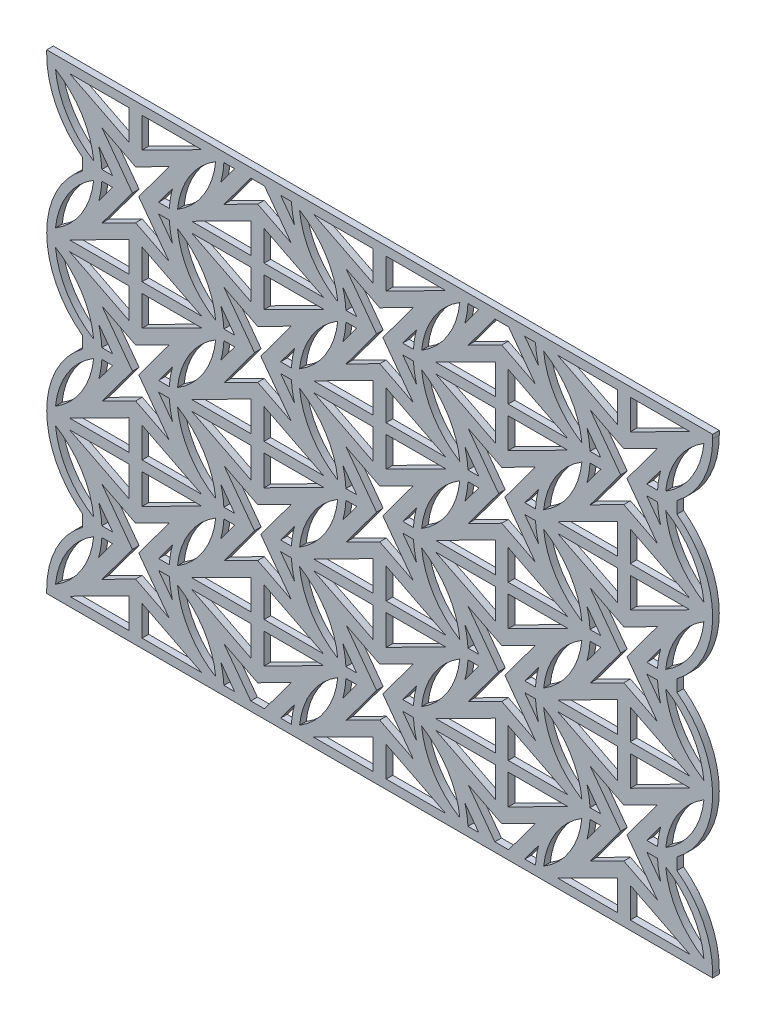
SolidWorks part; units mm, degrees
ref_plane "Front Plane" through (0, 0, 0) normal (0, 0, 1) x (1, 0, 0)
ref_plane "Top Plane" through (0, 0, 0) normal (0, 1, 0) x (1, 0, 0)
ref_plane "Right Plane" through (0, 0, 0) normal (1, 0, 0) x (0, 0, -1)
sketch "Sketch1" plane through (0, 0, 0) normal (0, 0, 1) x (1, 0, 0)
  line L1 (2.9839, -0.0761) -> (4.9328, -0.0761)
  line L3 (-17.2822, 14.8186) -> (-17.2822, 15.535) construction
  line L6 (14.9178, 15.535) -> (14.9178, 14.8186) construction
  line L8 (-5.3484, -0.0761) -> (-7.2973, -0.0761)
  line L9 (-17.2822, -13.1337) -> (-17.2822, -13.8502)
  line L10 (-5.3484, 1.761) -> (-7.8631, 5.1578)
  line L11 (-17.2822, -13.8502) -> (14.9178, -13.8502)
  line L13 (-10.8207, 1.9225) -> (-10.8207, -0.2376)
  line L16 (-17.2822, 14.8186) -> (14.9178, 14.8186) construction
  line L17 (10.7818, 13.9) -> (-0.0088, 13.9)
  line L21 (2.9839, 1.761) -> (5.4987, 5.1578)
  line L23 (-2.3557, 8.4501) -> (-13.1463, 13.9)
  line L24 (2.9839, -0.0761) -> (5.4987, -3.473)
  line L25 (2.9839, 1.761) -> (4.9328, 1.761)
  line L27 (-5.3484, -0.0761) -> (-7.8631, -3.473)
  line L28 (-5.3484, 1.761) -> (-7.2973, 1.761)
  line L30 (-17.2822, 15.535) -> (14.9178, 15.535) construction
  line L31 (-2.3557, 13.9) -> (-13.1463, 13.9)
  line L33 (14.9178, -13.8502) -> (14.9178, -13.1337) construction
  line L34 (-17.2822, -13.1337) -> (14.9178, -13.1337) construction
  line L36 (8.4563, 1.9225) -> (8.4563, -0.2376) construction
  line L40 (-0.0088, 8.4501) -> (10.7818, 13.9)
  line L41 (-1.1822, -3.5434) -> (4.9079, -6.6193)
  line L42 (4.9079, -6.6193) -> (-0.6161, 0.8424)
  line L43 (4.9079, 8.3041) -> (-0.6161, 0.8424)
  line L44 (-1.1822, 5.2282) -> (4.9079, 8.3041)
  line L45 (-1.1822, 5.2282) -> (-7.2724, 8.3041)
  line L46 (-7.2724, 8.3041) -> (-1.7483, 0.8424)
  line L47 (-7.2724, -6.6193) -> (-1.7483, 0.8424)
  line L48 (-1.1822, -3.5434) -> (-7.2724, -6.6193)
  line L49 (-1.7483, 0.8424) -> (49998.2517, 0.8424) construction
  line L50 (-1.1822, -3.5434) -> (-1.1822, 49996.4566) construction
  line L51 (-2.3557, 13.9) -> (-2.3557, 8.4501)
  line L52 (-0.0088, 13.9) -> (-0.0088, 8.4501)
  line L53 (-0.0088, -12.2152) -> (-0.0088, -6.7652)
  line L54 (10.7818, -12.2152) -> (-0.0088, -12.2152)
  line L55 (-0.0088, -6.7652) -> (10.7818, -12.2152)
  line L56 (-2.3557, -12.2152) -> (-2.3557, -6.7652)
  line L57 (-2.3557, -12.2152) -> (-13.1463, -12.2152)
  line L58 (-2.3557, -6.7652) -> (-13.1463, -12.2152)
  line L59 (32.8893, 27.8762) -> (22.0987, 27.8762)
  line L60 (32.8893, 1.761) -> (22.0987, 1.761)
  line L61 (37.0252, 29.5111) -> (37.0252, 28.7947) construction
  line L62 (19.7518, 27.8762) -> (8.9612, 27.8762)
  line L63 (19.7518, 27.8762) -> (19.7518, 22.4262)
  line L64 (4.8252, 0.126) -> (37.0252, 0.126) construction
  line L65 (16.7591, 13.9) -> (14.2443, 10.5031)
  line L66 (16.7591, 15.7371) -> (14.8102, 15.7371)
  line L67 (19.7518, 1.761) -> (8.9612, 1.761)
  line L68 (4.8252, 0.8424) -> (37.0252, 0.8424) construction
  line L69 (20.9252, 19.2043) -> (27.0154, 22.2802)
  line L70 (4.8252, 28.7947) -> (4.8252, 29.5111) construction
  line L71 (20.9252, 10.4328) -> (27.0154, 7.3569)
  line L72 (22.0987, 27.8762) -> (22.0987, 22.4262)
  line L73 (14.8351, 22.2802) -> (20.3591, 14.8186)
  line L74 (19.7518, 22.4262) -> (8.9612, 27.8762)
  line L75 (20.9252, 10.4328) -> (14.8351, 7.3569)
  line L76 (30.5638, 15.8986) -> (30.5638, 13.7385) construction
  line L77 (25.0914, 15.7371) -> (27.0403, 15.7371)
  line L78 (4.8252, 0.8424) -> (4.8252, 0.126) construction
  line L79 (25.0914, 13.9) -> (27.6061, 10.5031)
  line L80 (22.0987, 1.761) -> (22.0987, 7.2109)
  line L81 (11.2867, 15.8986) -> (11.2867, 13.7385) construction
  line L82 (25.0914, 15.7371) -> (27.6061, 19.134)
  line L83 (19.7518, 1.761) -> (19.7518, 7.2109)
  line L84 (37.0252, 0.126) -> (37.0252, 0.8424) construction
  line L85 (16.7591, 13.9) -> (14.8102, 13.9)
  line L86 (16.7591, 15.7371) -> (14.2443, 19.134)
  line L87 (22.0987, 7.2109) -> (32.8893, 1.761)
  line L88 (25.0914, 13.9) -> (27.0403, 13.9)
  line L89 (27.0154, 7.3569) -> (21.4913, 14.8186)
  line L90 (20.9252, 19.2043) -> (14.8351, 22.2802)
  line L91 (19.7518, 7.2109) -> (8.9612, 1.761)
  line L92 (4.8252, 28.7947) -> (37.0252, 28.7947) construction
  line L93 (22.0987, 22.4262) -> (32.8893, 27.8762)
  line L94 (27.0154, 22.2802) -> (21.4913, 14.8186)
  line L95 (14.8351, 7.3569) -> (20.3591, 14.8186)
  line L96 (4.8252, 29.5111) -> (37.0252, 29.5111) construction
  line L97 (54.9967, 41.8523) -> (44.2061, 41.8523)
  line L98 (54.9967, 15.7371) -> (44.2061, 15.7371)
  line L99 (59.1327, 43.4873) -> (59.1327, 42.7708) construction
  line L100 (41.8592, 41.8523) -> (31.0686, 41.8523)
  line L101 (41.8592, 41.8523) -> (41.8592, 36.4024)
  line L102 (26.9327, 14.1021) -> (59.1327, 14.1021) construction
  line L103 (38.8665, 27.8762) -> (36.3518, 24.4793)
  line L104 (38.8665, 29.7132) -> (36.9176, 29.7132)
  line L105 (41.8592, 15.7371) -> (31.0686, 15.7371)
  line L106 (26.9327, 14.8186) -> (59.1327, 14.8186) construction
  line L107 (43.0327, 33.1805) -> (49.1228, 36.2564)
  line L108 (26.9327, 42.7708) -> (26.9327, 43.4873) construction
  line L109 (43.0327, 24.4089) -> (49.1228, 21.333)
  line L110 (44.2061, 41.8523) -> (44.2061, 36.4024)
  line L111 (36.9425, 36.2564) -> (42.4666, 28.7947)
  line L112 (41.8592, 36.4024) -> (31.0686, 41.8523)
  line L113 (43.0327, 24.4089) -> (36.9425, 21.333)
  line L114 (52.6712, 29.8748) -> (52.6712, 27.7146) construction
  line L115 (47.1988, 29.7132) -> (49.1477, 29.7132)
  line L116 (26.9327, 14.8186) -> (26.9327, 14.1021) construction
  line L117 (47.1988, 27.8762) -> (49.7136, 24.4793)
  line L118 (44.2061, 15.7371) -> (44.2061, 21.187)
  line L119 (33.3942, 29.8748) -> (33.3942, 27.7146) construction
  line L120 (47.1988, 29.7132) -> (49.7136, 33.1101)
  line L121 (41.8592, 15.7371) -> (41.8592, 21.187)
  line L122 (59.1327, 14.1021) -> (59.1327, 14.8186) construction
  line L123 (38.8665, 27.8762) -> (36.9176, 27.8762)
  line L124 (38.8665, 29.7132) -> (36.3518, 33.1101)
  line L125 (44.2061, 21.187) -> (54.9967, 15.7371)
  line L126 (47.1988, 27.8762) -> (49.1477, 27.8762)
  line L127 (49.1228, 21.333) -> (43.5988, 28.7947)
  line L128 (43.0327, 33.1805) -> (36.9425, 36.2564)
  line L129 (41.8592, 21.187) -> (31.0686, 15.7371)
  line L130 (26.9327, 42.7708) -> (59.1327, 42.7708) construction
  line L131 (44.2061, 36.4024) -> (54.9967, 41.8523)
  line L132 (49.1228, 36.2564) -> (43.5988, 28.7947)
  line L133 (36.9425, 21.333) -> (42.4666, 28.7947)
  line L134 (26.9327, 43.4873) -> (59.1327, 43.4873) construction
  line L135 (77.1042, 55.8284) -> (66.3136, 55.8284)
  line L136 (77.1042, 29.7132) -> (66.3136, 29.7132)
  line L137 (81.2401, 57.4634) -> (81.2401, 56.747) construction
  line L138 (63.9667, 55.8284) -> (53.1761, 55.8284)
  line L139 (63.9667, 55.8284) -> (63.9667, 50.3785)
  line L140 (49.0401, 28.0782) -> (81.2401, 28.0782) construction
  line L141 (60.974, 41.8523) -> (58.4592, 38.4554)
  line L142 (60.974, 43.6894) -> (59.0251, 43.6894)
  line L143 (63.9667, 29.7132) -> (53.1761, 29.7132)
  line L144 (49.0401, 28.7947) -> (81.2401, 28.7947) construction
  line L145 (65.1401, 47.1566) -> (71.2303, 50.2325)
  line L146 (49.0401, 56.747) -> (49.0401, 57.4634) construction
  line L147 (65.1401, 38.3851) -> (71.2303, 35.3092)
  line L148 (66.3136, 55.8284) -> (66.3136, 50.3785)
  line L149 (59.05, 50.2325) -> (64.574, 42.7708)
  line L150 (63.9667, 50.3785) -> (53.1761, 55.8284)
  line L151 (65.1401, 38.3851) -> (59.05, 35.3092)
  line L152 (74.7786, 43.8509) -> (74.7786, 41.6908) construction
  line L153 (69.3063, 43.6894) -> (71.2552, 43.6894)
  line L154 (49.0401, 28.7947) -> (49.0401, 28.0782) construction
  line L155 (69.3063, 41.8523) -> (71.821, 38.4554)
  line L156 (66.3136, 29.7132) -> (66.3136, 35.1632)
  line L157 (55.5016, 43.8509) -> (55.5016, 41.6908) construction
  line L158 (69.3063, 43.6894) -> (71.821, 47.0862)
  line L159 (63.9667, 29.7132) -> (63.9667, 35.1632)
  line L160 (81.2401, 28.0782) -> (81.2401, 28.7947) construction
  line L161 (60.974, 41.8523) -> (59.0251, 41.8523)
  line L162 (60.974, 43.6894) -> (58.4592, 47.0862)
  line L163 (66.3136, 35.1632) -> (77.1042, 29.7132)
  line L164 (69.3063, 41.8523) -> (71.2552, 41.8523)
  line L165 (71.2303, 35.3092) -> (65.7062, 42.7708)
  line L166 (65.1401, 47.1566) -> (59.05, 50.2325)
  line L167 (63.9667, 35.1632) -> (53.1761, 29.7132)
  line L168 (49.0401, 56.747) -> (81.2401, 56.747) construction
  line L169 (66.3136, 50.3785) -> (77.1042, 55.8284)
  line L170 (71.2303, 50.2325) -> (65.7062, 42.7708)
  line L171 (59.05, 35.3092) -> (64.574, 42.7708)
  line L172 (49.0401, 57.4634) -> (81.2401, 57.4634) construction
  line L173 (99.2116, 69.8046) -> (88.421, 69.8046)
  line L174 (99.2116, 43.6894) -> (88.421, 43.6894)
  line L175 (103.3476, 71.4396) -> (103.3476, 70.7231)
  line L176 (86.0741, 69.8046) -> (75.2835, 69.8046)
  line L177 (86.0741, 69.8046) -> (86.0741, 64.3546)
  line L178 (71.1476, 42.0544) -> (103.3476, 42.0544) construction
  line L179 (83.0814, 55.8284) -> (80.5667, 52.4316)
  line L180 (83.0814, 57.6655) -> (81.1325, 57.6655)
  line L181 (86.0741, 43.6894) -> (75.2835, 43.6894)
  line L182 (71.1476, 42.7708) -> (103.3476, 42.7708) construction
  line L183 (87.2476, 61.1328) -> (93.3377, 64.2087)
  line L184 (71.1476, 70.7231) -> (71.1476, 71.4396) construction
  line L185 (87.2476, 52.3612) -> (93.3377, 49.2853)
  line L186 (88.421, 69.8046) -> (88.421, 64.3546)
  line L187 (81.1574, 64.2087) -> (86.6815, 56.747)
  line L188 (86.0741, 64.3546) -> (75.2835, 69.8046)
  line L189 (87.2476, 52.3612) -> (81.1574, 49.2853)
  line L190 (96.8861, 57.827) -> (96.8861, 55.6669)
  line L191 (91.4137, 57.6655) -> (93.3626, 57.6655)
  line L192 (71.1476, 42.7708) -> (71.1476, 42.0544) construction
  line L193 (91.4137, 55.8284) -> (93.9285, 52.4316)
  line L194 (88.421, 43.6894) -> (88.421, 49.1393)
  line L195 (77.6091, 57.827) -> (77.6091, 55.6669) construction
  line L196 (91.4137, 57.6655) -> (93.9285, 61.0624)
  line L197 (86.0741, 43.6894) -> (86.0741, 49.1393)
  line L198 (103.3476, 42.0544) -> (103.3476, 42.7708) construction
  line L199 (83.0814, 55.8284) -> (81.1325, 55.8284)
  line L200 (83.0814, 57.6655) -> (80.5667, 61.0624)
  line L201 (88.421, 49.1393) -> (99.2116, 43.6894)
  line L202 (91.4137, 55.8284) -> (93.3626, 55.8284)
  line L203 (93.3377, 49.2853) -> (87.8137, 56.747)
  line L204 (87.2476, 61.1328) -> (81.1574, 64.2087)
  line L205 (86.0741, 49.1393) -> (75.2835, 43.6894)
  line L206 (71.1476, 70.7231) -> (103.3476, 70.7231) construction
  line L207 (88.421, 64.3546) -> (99.2116, 69.8046)
  line L208 (93.3377, 64.2087) -> (87.8137, 56.747)
  line L209 (81.1574, 49.2853) -> (86.6815, 56.747)
  line L210 (71.1476, 71.4396) -> (103.3476, 71.4396)
  line L211 (20.9252, 47.1566) -> (27.0154, 50.2325)
  line L212 (4.8252, 56.747) -> (4.8252, 57.4634) construction
  line L213 (16.7591, 41.8523) -> (14.2443, 38.4554)
  line L214 (14.8351, 50.2325) -> (20.3591, 42.7708)
  line L215 (4.8252, 57.4634) -> (37.0252, 57.4634) construction
  line L216 (25.0914, 41.8523) -> (27.0403, 41.8523)
  line L217 (20.9252, 38.3851) -> (27.0154, 35.3092)
  line L218 (19.7518, 50.3785) -> (8.9612, 55.8284)
  line L219 (27.0154, 50.2325) -> (21.4913, 42.7708)
  line L220 (37.0252, 57.4634) -> (37.0252, 56.747) construction
  line L221 (16.7591, 43.6894) -> (14.2443, 47.0862)
  line L222 (22.0987, 29.7132) -> (22.0987, 35.1632)
  line L223 (11.2867, 43.8509) -> (11.2867, 41.6908) construction
  line L224 (22.0987, 50.3785) -> (32.8893, 55.8284)
  line L225 (22.0987, 55.8284) -> (22.0987, 50.3785)
  line L226 (19.7518, 35.1632) -> (8.9612, 29.7132)
  line L227 (25.0914, 43.6894) -> (27.0403, 43.6894)
  line L228 (22.0987, 35.1632) -> (32.8893, 29.7132)
  line L229 (4.8252, 56.747) -> (37.0252, 56.747) construction
  line L230 (19.7518, 55.8284) -> (19.7518, 50.3785)
  line L231 (20.9252, 47.1566) -> (14.8351, 50.2325)
  line L232 (4.8252, 28.0782) -> (37.0252, 28.0782) construction
  line L233 (25.0914, 43.6894) -> (27.6061, 47.0862)
  line L234 (19.7518, 29.7132) -> (8.9612, 29.7132)
  line L235 (16.7591, 41.8523) -> (14.8102, 41.8523)
  line L236 (27.0154, 35.3092) -> (21.4913, 42.7708)
  line L237 (4.8252, 28.7947) -> (37.0252, 28.7947) construction
  line L238 (19.7518, 55.8284) -> (8.9612, 55.8284)
  line L239 (20.9252, 38.3851) -> (14.8351, 35.3092)
  line L240 (37.0252, 28.0782) -> (37.0252, 28.7947) construction
  line L241 (25.0914, 41.8523) -> (27.6061, 38.4554)
  line L242 (32.8893, 29.7132) -> (22.0987, 29.7132)
  line L243 (14.8351, 35.3092) -> (20.3591, 42.7708)
  line L244 (32.8893, 55.8284) -> (22.0987, 55.8284)
  line L245 (4.8252, 28.7947) -> (4.8252, 28.0782) construction
  line L246 (16.7591, 43.6894) -> (14.8102, 43.6894)
  line L247 (19.7518, 29.7132) -> (19.7518, 35.1632)
  line L248 (30.5638, 43.8509) -> (30.5638, 41.6908) construction
  line L249 (43.0327, 61.1328) -> (49.1228, 64.2087)
  line L250 (26.9327, 70.7231) -> (26.9327, 71.4396) construction
  line L251 (38.8665, 55.8284) -> (36.3518, 52.4316)
  line L252 (36.9425, 64.2087) -> (42.4666, 56.747)
  line L253 (26.9327, 71.4396) -> (59.1327, 71.4396)
  line L254 (47.1988, 55.8284) -> (49.1477, 55.8284)
  line L255 (43.0327, 52.3612) -> (49.1228, 49.2853)
  line L256 (41.8592, 64.3546) -> (31.0686, 69.8046)
  line L257 (49.1228, 64.2087) -> (43.5988, 56.747)
  line L258 (59.1327, 71.4396) -> (59.1327, 70.7231) construction
  line L259 (38.8665, 57.6655) -> (36.3518, 61.0624)
  line L260 (44.2061, 43.6894) -> (44.2061, 49.1393)
  line L261 (33.3942, 57.827) -> (33.3942, 55.6669) construction
  line L262 (44.2061, 64.3546) -> (54.9967, 69.8046)
  line L263 (44.2061, 69.8046) -> (44.2061, 64.3546)
  line L264 (41.8592, 49.1393) -> (31.0686, 43.6894)
  line L265 (47.1988, 57.6655) -> (49.1477, 57.6655)
  line L266 (44.2061, 49.1393) -> (54.9967, 43.6894)
  line L267 (26.9327, 70.7231) -> (59.1327, 70.7231) construction
  line L268 (41.8592, 69.8046) -> (41.8592, 64.3546)
  line L269 (43.0327, 61.1328) -> (36.9425, 64.2087)
  line L270 (26.9327, 42.0544) -> (59.1327, 42.0544) construction
  line L271 (47.1988, 57.6655) -> (49.7136, 61.0624)
  line L272 (41.8592, 43.6894) -> (31.0686, 43.6894)
  line L273 (38.8665, 55.8284) -> (36.9176, 55.8284)
  line L274 (49.1228, 49.2853) -> (43.5988, 56.747)
  line L275 (26.9327, 42.7708) -> (59.1327, 42.7708) construction
  line L276 (41.8592, 69.8046) -> (31.0686, 69.8046)
  line L277 (43.0327, 52.3612) -> (36.9425, 49.2853)
  line L278 (59.1327, 42.0544) -> (59.1327, 42.7708) construction
  line L279 (47.1988, 55.8284) -> (49.7136, 52.4316)
  line L280 (54.9967, 43.6894) -> (44.2061, 43.6894)
  line L281 (36.9425, 49.2853) -> (42.4666, 56.747)
  line L282 (54.9967, 69.8046) -> (44.2061, 69.8046)
  line L283 (26.9327, 42.7708) -> (26.9327, 42.0544) construction
  line L284 (38.8665, 57.6655) -> (36.9176, 57.6655)
  line L285 (41.8592, 43.6894) -> (41.8592, 49.1393)
  line L286 (52.6712, 57.827) -> (52.6712, 55.6669) construction
  line L287 (-1.1822, 33.1805) -> (4.9079, 36.2564)
  line L288 (-17.2822, 42.7708) -> (-17.2822, 43.4873) construction
  line L289 (-5.3484, 27.8762) -> (-7.8631, 24.4793)
  line L290 (-7.2724, 36.2564) -> (-1.7483, 28.7947)
  line L291 (-17.2822, 43.4873) -> (14.9178, 43.4873) construction
  line L292 (2.9839, 27.8762) -> (4.9328, 27.8762)
  line L293 (-1.1822, 24.4089) -> (4.9079, 21.333)
  line L294 (-2.3557, 36.4024) -> (-13.1463, 41.8523)
  line L295 (4.9079, 36.2564) -> (-0.6161, 28.7947)
  line L296 (14.9178, 43.4873) -> (14.9178, 42.7708) construction
  line L297 (-5.3484, 29.7132) -> (-7.8631, 33.1101)
  line L298 (-0.0088, 15.7371) -> (-0.0088, 21.187)
  line L299 (-10.8207, 29.8748) -> (-10.8207, 27.7146)
  line L300 (-0.0088, 36.4024) -> (10.7818, 41.8523)
  line L301 (-0.0088, 41.8523) -> (-0.0088, 36.4024)
  line L302 (-2.3557, 21.187) -> (-13.1463, 15.7371)
  line L303 (2.9839, 29.7132) -> (4.9328, 29.7132)
  line L304 (-0.0088, 21.187) -> (10.7818, 15.7371)
  line L305 (-17.2822, 42.7708) -> (14.9178, 42.7708) construction
  line L306 (-2.3557, 41.8523) -> (-2.3557, 36.4024)
  line L307 (-1.1822, 33.1805) -> (-7.2724, 36.2564)
  line L308 (-17.2822, 14.1021) -> (14.9178, 14.1021) construction
  line L309 (2.9839, 29.7132) -> (5.4987, 33.1101)
  line L310 (-2.3557, 15.7371) -> (-13.1463, 15.7371)
  line L311 (-5.3484, 27.8762) -> (-7.2973, 27.8762)
  line L312 (4.9079, 21.333) -> (-0.6161, 28.7947)
  line L313 (-17.2822, 14.8186) -> (14.9178, 14.8186) construction
  line L314 (-2.3557, 41.8523) -> (-13.1463, 41.8523)
  line L315 (-1.1822, 24.4089) -> (-7.2724, 21.333)
  line L316 (14.9178, 14.1021) -> (14.9178, 14.8186) construction
  line L317 (2.9839, 27.8762) -> (5.4987, 24.4793)
  line L318 (10.7818, 15.7371) -> (-0.0088, 15.7371)
  line L319 (-7.2724, 21.333) -> (-1.7483, 28.7947)
  line L320 (10.7818, 41.8523) -> (-0.0088, 41.8523)
  line L321 (-17.2822, 14.8186) -> (-17.2822, 14.1021) construction
  line L322 (-5.3484, 29.7132) -> (-7.2973, 29.7132)
  line L323 (-2.3557, 15.7371) -> (-2.3557, 21.187)
  line L324 (8.4563, 29.8748) -> (8.4563, 27.7146) construction
  line L326 (49.0401, 84.6993) -> (49.0401, 85.4157) construction
  line L327 (60.974, 69.8046) -> (58.4592, 66.4077)
  line L329 (49.0401, 85.4157) -> (81.2401, 85.4157) construction
  line L330 (69.3063, 69.8046) -> (71.2552, 69.8046)
  line L331 (65.1401, 66.3373) -> (71.2303, 63.2614)
  line L332 (63.9667, 78.3308) -> (53.1761, 83.7807) construction
  line L334 (81.2401, 85.4157) -> (81.2401, 84.6993) construction
  line L335 (60.974, 71.6416) -> (58.4592, 75.0385) construction
  line L336 (66.3136, 57.6655) -> (66.3136, 63.1155)
  line L337 (55.5016, 71.8032) -> (55.5016, 69.6431) construction
  line L338 (66.3136, 78.3308) -> (77.1042, 83.7807) construction
  line L339 (66.3136, 83.7807) -> (66.3136, 78.3308) construction
  line L340 (63.9667, 63.1155) -> (53.1761, 57.6655)
  line L341 (69.3063, 71.6416) -> (71.2552, 71.6416) construction
  line L342 (66.3136, 63.1155) -> (77.1042, 57.6655)
  line L343 (49.0401, 84.6993) -> (81.2401, 84.6993) construction
  line L344 (63.9667, 83.7807) -> (63.9667, 78.3308) construction
  line L346 (49.0401, 56.0305) -> (81.2401, 56.0305) construction
  line L347 (69.3063, 71.6416) -> (71.821, 75.0385) construction
  line L348 (63.9667, 57.6655) -> (53.1761, 57.6655)
  line L349 (60.974, 69.8046) -> (59.0251, 69.8046)
  line L350 (71.2303, 63.2614) -> (66.3862, 69.8046)
  line L351 (49.0401, 56.747) -> (81.2401, 56.747) construction
  line L352 (63.9667, 83.7807) -> (53.1761, 83.7807) construction
  line L353 (65.1401, 66.3373) -> (59.05, 63.2614)
  line L354 (81.2401, 56.0305) -> (81.2401, 56.747) construction
  line L355 (69.3063, 69.8046) -> (71.821, 66.4077)
  line L356 (77.1042, 57.6655) -> (66.3136, 57.6655)
  line L357 (59.05, 63.2614) -> (63.894, 69.8046)
  line L358 (77.1042, 83.7807) -> (66.3136, 83.7807) construction
  line L359 (49.0401, 56.747) -> (49.0401, 56.0305) construction
  line L360 (60.974, 71.6416) -> (59.0251, 71.6416) construction
  line L361 (63.9667, 57.6655) -> (63.9667, 63.1155)
  line L362 (74.7786, 71.8032) -> (74.7786, 69.6431) construction
  line L364 (4.8252, 84.6993) -> (4.8252, 85.4157) construction
  line L365 (16.7591, 69.8046) -> (14.2443, 66.4077)
  line L367 (4.8252, 85.4157) -> (37.0252, 85.4157) construction
  line L368 (25.0914, 69.8046) -> (27.0403, 69.8046)
  line L369 (20.9252, 66.3373) -> (27.0154, 63.2614)
  line L370 (19.7518, 78.3308) -> (8.9612, 83.7807) construction
  line L372 (37.0252, 85.4157) -> (37.0252, 84.6993) construction
  line L373 (16.7591, 71.6416) -> (14.2443, 75.0385) construction
  line L374 (22.0987, 57.6655) -> (22.0987, 63.1155)
  line L375 (11.2867, 71.8032) -> (11.2867, 69.6431) construction
  line L376 (22.0987, 78.3308) -> (32.8893, 83.7807) construction
  line L377 (22.0987, 83.7807) -> (22.0987, 78.3308) construction
  line L378 (19.7518, 63.1155) -> (8.9612, 57.6655)
  line L379 (25.0914, 71.6416) -> (27.0403, 71.6416) construction
  line L380 (22.0987, 63.1155) -> (32.8893, 57.6655)
  line L381 (4.8252, 84.6993) -> (37.0252, 84.6993) construction
  line L382 (19.7518, 83.7807) -> (19.7518, 78.3308) construction
  line L384 (4.8252, 56.0305) -> (37.0252, 56.0305) construction
  line L385 (25.0914, 71.6416) -> (27.6061, 75.0385) construction
  line L386 (19.7518, 57.6655) -> (8.9612, 57.6655)
  line L387 (16.7591, 69.8046) -> (14.8102, 69.8046)
  line L388 (27.0154, 63.2614) -> (22.1713, 69.8046)
  line L389 (4.8252, 56.747) -> (37.0252, 56.747) construction
  line L390 (19.7518, 83.7807) -> (8.9612, 83.7807) construction
  line L391 (20.9252, 66.3373) -> (14.8351, 63.2614)
  line L392 (37.0252, 56.0305) -> (37.0252, 56.747) construction
  line L393 (25.0914, 69.8046) -> (27.6061, 66.4077)
  line L394 (32.8893, 57.6655) -> (22.0987, 57.6655)
  line L395 (14.8351, 63.2614) -> (19.6791, 69.8046)
  line L396 (32.8893, 83.7807) -> (22.0987, 83.7807) construction
  line L397 (4.8252, 56.747) -> (4.8252, 56.0305) construction
  line L398 (16.7591, 71.6416) -> (14.8102, 71.6416) construction
  line L399 (19.7518, 57.6655) -> (19.7518, 63.1155)
  line L400 (30.5638, 71.8032) -> (30.5638, 69.6431) construction
  line L401 (-1.1822, 61.1328) -> (4.9079, 64.2087)
  line L402 (-17.2822, 70.7231) -> (-17.2822, 71.4396)
  line L403 (-5.3484, 55.8284) -> (-7.8631, 52.4316)
  line L404 (-7.2724, 64.2087) -> (-1.7483, 56.747)
  line L405 (-17.2822, 71.4396) -> (14.9178, 71.4396)
  line L406 (2.9839, 55.8284) -> (4.9328, 55.8284)
  line L407 (-1.1822, 52.3612) -> (4.9079, 49.2853)
  line L408 (-2.3557, 64.3546) -> (-13.1463, 69.8046)
  line L409 (4.9079, 64.2087) -> (-0.6161, 56.747)
  line L410 (14.9178, 71.4396) -> (14.9178, 70.7231) construction
  line L411 (-5.3484, 57.6655) -> (-7.8631, 61.0624)
  line L412 (-0.0088, 43.6894) -> (-0.0088, 49.1393)
  line L413 (-10.8207, 57.827) -> (-10.8207, 55.6669)
  line L414 (-0.0088, 64.3546) -> (10.7818, 69.8046)
  line L415 (-0.0088, 69.8046) -> (-0.0088, 64.3546)
  line L416 (-2.3557, 49.1393) -> (-13.1463, 43.6894)
  line L417 (2.9839, 57.6655) -> (4.9328, 57.6655)
  line L418 (-0.0088, 49.1393) -> (10.7818, 43.6894)
  line L419 (-17.2822, 70.7231) -> (14.9178, 70.7231) construction
  line L420 (-2.3557, 69.8046) -> (-2.3557, 64.3546)
  line L421 (-1.1822, 61.1328) -> (-7.2724, 64.2087)
  line L422 (-17.2822, 42.0544) -> (14.9178, 42.0544) construction
  line L423 (2.9839, 57.6655) -> (5.4987, 61.0624)
  line L424 (-2.3557, 43.6894) -> (-13.1463, 43.6894)
  line L425 (-5.3484, 55.8284) -> (-7.2973, 55.8284)
  line L426 (4.9079, 49.2853) -> (-0.6161, 56.747)
  line L427 (-17.2822, 42.7708) -> (14.9178, 42.7708) construction
  line L428 (-2.3557, 69.8046) -> (-13.1463, 69.8046)
  line L429 (-1.1822, 52.3612) -> (-7.2724, 49.2853)
  line L430 (14.9178, 42.0544) -> (14.9178, 42.7708) construction
  line L431 (2.9839, 55.8284) -> (5.4987, 52.4316)
  line L432 (10.7818, 43.6894) -> (-0.0088, 43.6894)
  line L433 (-7.2724, 49.2853) -> (-1.7483, 56.747)
  line L434 (10.7818, 69.8046) -> (-0.0088, 69.8046)
  line L435 (-17.2822, 42.7708) -> (-17.2822, 42.0544) construction
  line L436 (-5.3484, 57.6655) -> (-7.2973, 57.6655)
  line L437 (-2.3557, 43.6894) -> (-2.3557, 49.1393)
  line L438 (8.4563, 57.827) -> (8.4563, 55.6669) construction
  line L439 (47.1988, 1.761) -> (49.7136, 5.1578)
  line L440 (54.9967, -12.2152) -> (44.2061, -12.2152)
  line L441 (52.6712, 1.9225) -> (52.6712, -0.2376) construction
  line L442 (44.2061, 13.9) -> (44.2061, 8.4501)
  line L443 (41.8592, -12.2152) -> (41.8592, -6.7652)
  line L444 (59.1327, 15.535) -> (59.1327, 14.8186) construction
  line L445 (49.1228, 8.3041) -> (43.5988, 0.8424)
  line L446 (26.9327, -13.1337) -> (59.1327, -13.1337) construction
  line L447 (41.8592, 13.9) -> (41.8592, 8.4501)
  line L448 (41.8592, -6.7652) -> (31.0686, -12.2152)
  line L449 (41.8592, 13.9) -> (31.0686, 13.9)
  line L450 (33.3942, 1.9225) -> (33.3942, -0.2376) construction
  line L451 (43.0327, -3.5434) -> (49.1228, -6.6193)
  line L452 (26.9327, 14.8186) -> (26.9327, 15.535) construction
  line L453 (38.8665, -0.0761) -> (36.9176, -0.0761)
  line L454 (43.0327, 5.2282) -> (36.9425, 8.3041)
  line L455 (26.9327, 15.535) -> (59.1327, 15.535) construction
  line L456 (44.2061, 8.4501) -> (54.9967, 13.9)
  line L457 (43.0327, -3.5434) -> (36.9425, -6.6193)
  line L458 (26.9327, 14.8186) -> (59.1327, 14.8186) construction
  line L459 (41.8592, 8.4501) -> (31.0686, 13.9)
  line L460 (59.1327, -13.8502) -> (59.1327, -13.1337) construction
  line L461 (54.9967, 13.9) -> (44.2061, 13.9)
  line L462 (47.1988, -0.0761) -> (49.7136, -3.473)
  line L463 (44.2061, -12.2152) -> (44.2061, -6.7652)
  line L464 (26.9327, -13.1337) -> (26.9327, -13.8502) construction
  line L465 (49.1228, -6.6193) -> (43.5988, 0.8424)
  line L466 (41.8592, -12.2152) -> (31.0686, -12.2152)
  line L467 (26.9327, -13.8502) -> (59.1327, -13.8502)
  line L468 (36.9425, 8.3041) -> (42.4666, 0.8424)
  line L469 (38.8665, -0.0761) -> (36.3518, -3.473)
  line L470 (47.1988, 1.761) -> (49.1477, 1.761)
  line L471 (47.1988, -0.0761) -> (49.1477, -0.0761)
  line L472 (43.0327, 5.2282) -> (49.1228, 8.3041)
  line L473 (38.8665, 1.761) -> (36.3518, 5.1578)
  line L474 (36.9425, -6.6193) -> (42.4666, 0.8424)
  line L475 (38.8665, 1.761) -> (36.9176, 1.761)
  line L476 (44.2061, -6.7652) -> (54.9967, -12.2152)
  line L477 (69.3063, 15.7371) -> (71.821, 19.134)
  line L478 (77.1042, 1.761) -> (66.3136, 1.761)
  line L479 (74.7786, 15.8986) -> (74.7786, 13.7385) construction
  line L480 (66.3136, 27.8762) -> (66.3136, 22.4262)
  line L481 (63.9667, 1.761) -> (63.9667, 7.2109)
  line L482 (81.2401, 29.5111) -> (81.2401, 28.7947) construction
  line L483 (71.2303, 22.2802) -> (65.7062, 14.8186)
  line L484 (49.0401, 0.8424) -> (81.2401, 0.8424) construction
  line L485 (63.9667, 27.8762) -> (63.9667, 22.4262)
  line L486 (63.9667, 7.2109) -> (53.1761, 1.761)
  line L487 (63.9667, 27.8762) -> (53.1761, 27.8762)
  line L488 (55.5016, 15.8986) -> (55.5016, 13.7385) construction
  line L489 (65.1401, 10.4328) -> (71.2303, 7.3569)
  line L490 (49.0401, 28.7947) -> (49.0401, 29.5111) construction
  line L491 (60.974, 13.9) -> (59.0251, 13.9)
  line L492 (65.1401, 19.2043) -> (59.05, 22.2802)
  line L493 (49.0401, 29.5111) -> (81.2401, 29.5111) construction
  line L494 (66.3136, 22.4262) -> (77.1042, 27.8762)
  line L495 (65.1401, 10.4328) -> (59.05, 7.3569)
  line L496 (49.0401, 28.7947) -> (81.2401, 28.7947) construction
  line L497 (63.9667, 22.4262) -> (53.1761, 27.8762)
  line L498 (81.2401, 0.126) -> (81.2401, 0.8424) construction
  line L499 (77.1042, 27.8762) -> (66.3136, 27.8762)
  line L500 (69.3063, 13.9) -> (71.821, 10.5031)
  line L501 (66.3136, 1.761) -> (66.3136, 7.2109)
  line L502 (49.0401, 0.8424) -> (49.0401, 0.126) construction
  line L503 (71.2303, 7.3569) -> (65.7062, 14.8186)
  line L504 (63.9667, 1.761) -> (53.1761, 1.761)
  line L505 (49.0401, 0.126) -> (81.2401, 0.126) construction
  line L506 (59.05, 22.2802) -> (64.574, 14.8186)
  line L507 (60.974, 13.9) -> (58.4592, 10.5031)
  line L508 (69.3063, 15.7371) -> (71.2552, 15.7371)
  line L509 (69.3063, 13.9) -> (71.2552, 13.9)
  line L510 (65.1401, 19.2043) -> (71.2303, 22.2802)
  line L511 (60.974, 15.7371) -> (58.4592, 19.134)
  line L512 (59.05, 7.3569) -> (64.574, 14.8186)
  line L513 (60.974, 15.7371) -> (59.0251, 15.7371)
  line L514 (66.3136, 7.2109) -> (77.1042, 1.761)
  line L515 (91.4137, 29.7132) -> (93.9285, 33.1101)
  line L516 (99.2116, 15.7371) -> (88.421, 15.7371)
  line L517 (96.8861, 29.8748) -> (96.8861, 27.7146)
  line L518 (88.421, 41.8523) -> (88.421, 36.4024)
  line L519 (86.0741, 15.7371) -> (86.0741, 21.187)
  line L520 (103.3476, 43.4873) -> (103.3476, 42.7708) construction
  line L521 (93.3377, 36.2564) -> (87.8137, 28.7947)
  line L522 (71.1476, 14.8186) -> (103.3476, 14.8186) construction
  line L523 (86.0741, 41.8523) -> (86.0741, 36.4024)
  line L524 (86.0741, 21.187) -> (75.2835, 15.7371)
  line L525 (86.0741, 41.8523) -> (75.2835, 41.8523)
  line L526 (77.6091, 29.8748) -> (77.6091, 27.7146) construction
  line L527 (87.2476, 24.4089) -> (93.3377, 21.333)
  line L528 (71.1476, 42.7708) -> (71.1476, 43.4873) construction
  line L529 (83.0814, 27.8762) -> (81.1325, 27.8762)
  line L530 (87.2476, 33.1805) -> (81.1574, 36.2564)
  line L531 (71.1476, 43.4873) -> (103.3476, 43.4873) construction
  line L532 (88.421, 36.4024) -> (99.2116, 41.8523)
  line L533 (87.2476, 24.4089) -> (81.1574, 21.333)
  line L534 (71.1476, 42.7708) -> (103.3476, 42.7708) construction
  line L535 (86.0741, 36.4024) -> (75.2835, 41.8523)
  line L536 (103.3476, 14.1021) -> (103.3476, 14.8186) construction
  line L537 (99.2116, 41.8523) -> (88.421, 41.8523)
  line L538 (91.4137, 27.8762) -> (93.9285, 24.4793)
  line L539 (88.421, 15.7371) -> (88.421, 21.187)
  line L540 (71.1476, 14.8186) -> (71.1476, 14.1021) construction
  line L541 (93.3377, 21.333) -> (87.8137, 28.7947)
  line L542 (86.0741, 15.7371) -> (75.2835, 15.7371)
  line L543 (71.1476, 14.1021) -> (103.3476, 14.1021) construction
  line L544 (81.1574, 36.2564) -> (86.6815, 28.7947)
  line L545 (83.0814, 27.8762) -> (80.5667, 24.4793)
  line L546 (91.4137, 29.7132) -> (93.3626, 29.7132)
  line L547 (91.4137, 27.8762) -> (93.3626, 27.8762)
  line L548 (87.2476, 33.1805) -> (93.3377, 36.2564)
  line L549 (83.0814, 29.7132) -> (80.5667, 33.1101)
  line L550 (81.1574, 21.333) -> (86.6815, 28.7947)
  line L551 (83.0814, 29.7132) -> (81.1325, 29.7132)
  line L552 (88.421, 21.187) -> (99.2116, 15.7371)
  line L553 (83.0814, 1.761) -> (80.5667, 5.1578)
  line L554 (87.2476, -3.5434) -> (81.1574, -6.6193)
  line L555 (71.1476, 15.535) -> (103.3476, 15.535) construction
  line L556 (86.0741, 8.4501) -> (75.2835, 13.9)
  line L557 (88.421, 13.9) -> (88.421, 8.4501)
  line L558 (91.4137, -0.0761) -> (93.9285, -3.473)
  line L559 (81.1574, 8.3041) -> (86.6815, 0.8424)
  line L560 (83.0814, 1.761) -> (81.1325, 1.761)
  line L561 (88.421, -6.7652) -> (99.2116, -12.2152)
  line L562 (71.1476, -13.1337) -> (71.1476, -13.8502) construction
  line L563 (93.3377, 8.3041) -> (87.8137, 0.8424)
  line L564 (86.0741, -6.7652) -> (75.2835, -12.2152)
  line L565 (71.1476, 14.8186) -> (103.3476, 14.8186) construction
  line L566 (93.3377, -6.6193) -> (87.8137, 0.8424)
  line L567 (103.3476, -13.8502) -> (103.3476, -13.1337)
  line L568 (88.421, 8.4501) -> (99.2116, 13.9)
  line L569 (87.2476, -3.5434) -> (93.3377, -6.6193)
  line L570 (83.0814, -0.0761) -> (81.1325, -0.0761)
  line L571 (99.2116, 13.9) -> (88.421, 13.9)
  line L572 (87.2476, 5.2282) -> (81.1574, 8.3041)
  line L573 (96.8861, 1.9225) -> (96.8861, -0.2376)
  line L574 (91.4137, 1.761) -> (93.9285, 5.1578)
  line L575 (81.1574, -6.6193) -> (86.6815, 0.8424)
  line L576 (71.1476, 14.8186) -> (71.1476, 15.535) construction
  line L577 (91.4137, -0.0761) -> (93.3626, -0.0761)
  line L578 (88.421, -12.2152) -> (88.421, -6.7652)
  line L579 (91.4137, 1.761) -> (93.3626, 1.761)
  line L580 (99.2116, -12.2152) -> (88.421, -12.2152)
  line L581 (103.3476, 15.535) -> (103.3476, 14.8186) construction
  line L582 (86.0741, 13.9) -> (75.2835, 13.9)
  line L583 (86.0741, -12.2152) -> (75.2835, -12.2152)
  line L584 (71.1476, -13.8502) -> (103.3476, -13.8502)
  line L585 (86.0741, 13.9) -> (86.0741, 8.4501)
  line L586 (77.6091, 1.9225) -> (77.6091, -0.2376) construction
  line L587 (86.0741, -12.2152) -> (86.0741, -6.7652)
  line L588 (83.0814, -0.0761) -> (80.5667, -3.473)
  line L589 (87.2476, 5.2282) -> (93.3377, 8.3041)
  line L590 (71.1476, -13.1337) -> (103.3476, -13.1337) construction
  line L591 (16.7591, -12.2152) -> (14.2443, -8.8183)
  line L593 (4.8252, 1.5589) -> (37.0252, 1.5589) construction
  line L594 (19.7518, -5.5261) -> (8.9612, -0.0761)
  line L595 (22.0987, -0.0761) -> (22.0987, -5.5261)
  line L596 (25.0914, -14.0523) -> (27.6061, -17.4491) construction
  line L597 (14.8351, -5.672) -> (19.6791, -12.2152)
  line L598 (16.7591, -12.2152) -> (14.8102, -12.2152)
  line L599 (22.0987, -20.7414) -> (32.8893, -26.1913) construction
  line L600 (4.8252, -27.1099) -> (4.8252, -27.8263) construction
  line L601 (27.0154, -5.672) -> (22.1713, -12.2152)
  line L602 (19.7518, -20.7414) -> (8.9612, -26.1913) construction
  line L603 (4.8252, 0.8424) -> (37.0252, 0.8424) construction
  line L605 (37.0252, -27.8263) -> (37.0252, -27.1099) construction
  line L606 (22.0987, -5.5261) -> (32.8893, -0.0761)
  line L608 (16.7591, -14.0523) -> (14.8102, -14.0523) construction
  line L609 (32.8893, -0.0761) -> (22.0987, -0.0761)
  line L610 (20.9252, -8.7479) -> (14.8351, -5.672)
  line L611 (30.5638, -12.0537) -> (30.5638, -14.2138) construction
  line L612 (25.0914, -12.2152) -> (27.6061, -8.8183)
  line L614 (4.8252, 0.8424) -> (4.8252, 1.5589) construction
  line L615 (25.0914, -14.0523) -> (27.0403, -14.0523) construction
  line L616 (22.0987, -26.1913) -> (22.0987, -20.7414) construction
  line L617 (25.0914, -12.2152) -> (27.0403, -12.2152)
  line L618 (32.8893, -26.1913) -> (22.0987, -26.1913) construction
  line L619 (37.0252, 1.5589) -> (37.0252, 0.8424) construction
  line L620 (19.7518, -0.0761) -> (8.9612, -0.0761)
  line L621 (19.7518, -26.1913) -> (8.9612, -26.1913) construction
  line L622 (4.8252, -27.8263) -> (37.0252, -27.8263) construction
  line L623 (19.7518, -0.0761) -> (19.7518, -5.5261)
  line L624 (11.2867, -12.0537) -> (11.2867, -14.2138) construction
  line L625 (19.7518, -26.1913) -> (19.7518, -20.7414) construction
  line L626 (16.7591, -14.0523) -> (14.2443, -17.4491) construction
  line L627 (20.9252, -8.7479) -> (27.0154, -5.672)
  line L628 (4.8252, -27.1099) -> (37.0252, -27.1099) construction
  line L629 (60.974, -12.2152) -> (58.4592, -8.8183)
  line L631 (49.0401, 1.5589) -> (81.2401, 1.5589) construction
  line L632 (63.9667, -5.5261) -> (53.1761, -0.0761)
  line L633 (66.3136, -0.0761) -> (66.3136, -5.5261)
  line L634 (69.3063, -14.0523) -> (71.821, -17.4491) construction
  line L635 (59.05, -5.672) -> (63.894, -12.2152)
  line L636 (60.974, -12.2152) -> (59.0251, -12.2152)
  line L637 (66.3136, -20.7414) -> (77.1042, -26.1913) construction
  line L638 (49.0401, -27.1099) -> (49.0401, -27.8263) construction
  line L639 (71.2303, -5.672) -> (66.3862, -12.2152)
  line L640 (63.9667, -20.7414) -> (53.1761, -26.1913) construction
  line L641 (49.0401, 0.8424) -> (81.2401, 0.8424) construction
  line L643 (81.2401, -27.8263) -> (81.2401, -27.1099) construction
  line L644 (66.3136, -5.5261) -> (77.1042, -0.0761)
  line L646 (60.974, -14.0523) -> (59.0251, -14.0523) construction
  line L647 (77.1042, -0.0761) -> (66.3136, -0.0761)
  line L648 (65.1401, -8.7479) -> (59.05, -5.672)
  line L649 (74.7786, -12.0537) -> (74.7786, -14.2138) construction
  line L650 (69.3063, -12.2152) -> (71.821, -8.8183)
  line L652 (49.0401, 0.8424) -> (49.0401, 1.5589) construction
  line L653 (69.3063, -14.0523) -> (71.2552, -14.0523) construction
  line L654 (66.3136, -26.1913) -> (66.3136, -20.7414) construction
  line L655 (69.3063, -12.2152) -> (71.2552, -12.2152)
  line L656 (77.1042, -26.1913) -> (66.3136, -26.1913) construction
  line L657 (81.2401, 1.5589) -> (81.2401, 0.8424) construction
  line L658 (63.9667, -0.0761) -> (53.1761, -0.0761)
  line L659 (63.9667, -26.1913) -> (53.1761, -26.1913) construction
  line L660 (49.0401, -27.8263) -> (81.2401, -27.8263) construction
  line L661 (63.9667, -0.0761) -> (63.9667, -5.5261)
  line L662 (55.5016, -12.0537) -> (55.5016, -14.2138) construction
  line L663 (63.9667, -26.1913) -> (63.9667, -20.7414) construction
  line L664 (60.974, -14.0523) -> (58.4592, -17.4491) construction
  line L665 (65.1401, -8.7479) -> (71.2303, -5.672)
  line L666 (49.0401, -27.1099) -> (81.2401, -27.1099) construction
  line L667 (19.6791, 69.8046) -> (22.1713, 69.8046)
  line L668 (14.9178, 71.4396) -> (26.9327, 71.4396)
  line L669 (63.894, 69.8046) -> (66.3862, 69.8046)
  line L670 (59.1327, 71.4396) -> (71.1476, 71.4396)
  line L671 (14.9178, -13.8502) -> (26.9327, -13.8502)
  line L672 (59.1327, -13.8502) -> (71.1476, -13.8502)
  line L673 (63.894, -12.2152) -> (66.3862, -12.2152)
  line L674 (19.6791, -12.2152) -> (22.1713, -12.2152)
  arc A0 (-7.2973, -0.0761) -> (-7.8631, -3.473) centre (-23.2897, 0.8424) cw
  arc A1 (6.4127, -0.6745) -> (13.3303, -11.6168) centre (-1.1822, -13.1337) cw
  arc A2 (-15.6947, -11.6168) -> (-8.7771, -0.6745) centre (-23.2897, 0.8424) ccw
  arc A3 (6.4127, 2.3594) -> (13.3303, 13.3016) centre (-1.1822, 14.8186) ccw
  arc A4 (14.9178, 14.8186) -> (8.4563, 1.9225) centre (-1.1822, 14.8186) cw construction
  arc A5 (-17.2822, 14.8186) -> (-10.8207, 1.9225) centre (-1.1822, 14.8186) ccw
  arc A6 (-15.6947, 13.3016) -> (-8.7771, 2.3594) centre (-23.2897, 0.8424) cw
  arc A7 (-8.7771, -0.6745) -> (-15.6947, -11.6168) centre (-1.1822, -13.1337) ccw
  arc A8 (13.3303, -11.6168) -> (6.4127, -0.6745) centre (20.9252, 0.8424) cw
  arc A9 (-7.2973, 1.761) -> (-7.8631, 5.1578) centre (-23.2897, 0.8424) ccw
  arc A10 (8.4563, -0.2376) -> (14.9178, -13.1337) centre (-1.1822, -13.1337) cw construction
  arc A11 (-8.7771, 2.3594) -> (-15.6947, 13.3016) centre (-1.1822, 14.8186) cw
  arc A12 (4.9328, -0.0761) -> (5.4987, -3.473) centre (20.9252, 0.8424) ccw
  arc A13 (4.9328, 1.761) -> (5.4987, 5.1578) centre (20.9252, 0.8424) cw
  arc A14 (-10.8207, -0.2376) -> (-17.2822, -13.1337) centre (-1.1822, -13.1337) ccw
  arc A15 (13.3303, 13.3016) -> (6.4127, 2.3594) centre (20.9252, 0.8424) ccw
  arc A16 (11.2867, 13.7385) -> (4.8252, 0.8424) centre (20.9252, 0.8424) ccw construction
  arc A17 (14.8102, 15.7371) -> (14.2443, 19.134) centre (-1.1822, 14.8186) ccw
  arc A18 (27.0403, 15.7371) -> (27.6061, 19.134) centre (43.0327, 14.8186) cw
  arc A20 (14.8102, 13.9) -> (14.2443, 10.5031) centre (-1.1822, 14.8186) cw
  arc A22 (37.0252, 28.7947) -> (30.5638, 15.8986) centre (20.9252, 28.7947) cw construction
  arc A23 (35.4378, 2.3594) -> (28.5202, 13.3016) centre (43.0327, 14.8186) cw
  arc A24 (4.8252, 28.7947) -> (11.2867, 15.8986) centre (20.9252, 28.7947) ccw construction
  arc A25 (27.0403, 13.9) -> (27.6061, 10.5031) centre (43.0327, 14.8186) ccw
  arc A26 (28.5202, 13.3016) -> (35.4378, 2.3594) centre (20.9252, 0.8424) cw
  arc A27 (35.4378, 27.2778) -> (28.5202, 16.3355) centre (43.0327, 14.8186) ccw
  arc A28 (28.5202, 16.3355) -> (35.4378, 27.2778) centre (20.9252, 28.7947) ccw
  arc A30 (30.5638, 13.7385) -> (37.0252, 0.8424) centre (20.9252, 0.8424) cw construction
  arc A32 (33.3942, 27.7146) -> (26.9327, 14.8186) centre (43.0327, 14.8186) ccw construction
  arc A33 (36.9176, 29.7132) -> (36.3518, 33.1101) centre (20.9252, 28.7947) ccw
  arc A34 (49.1477, 29.7132) -> (49.7136, 33.1101) centre (65.1401, 28.7947) cw
  arc A36 (36.9176, 27.8762) -> (36.3518, 24.4793) centre (20.9252, 28.7947) cw
  arc A38 (59.1327, 42.7708) -> (52.6712, 29.8748) centre (43.0327, 42.7708) cw construction
  arc A39 (57.5452, 16.3355) -> (50.6276, 27.2778) centre (65.1401, 28.7947) cw
  arc A40 (26.9327, 42.7708) -> (33.3942, 29.8748) centre (43.0327, 42.7708) ccw construction
  arc A41 (49.1477, 27.8762) -> (49.7136, 24.4793) centre (65.1401, 28.7947) ccw
  arc A42 (50.6276, 27.2778) -> (57.5452, 16.3355) centre (43.0327, 14.8186) cw
  arc A43 (57.5452, 41.2539) -> (50.6276, 30.3116) centre (65.1401, 28.7947) ccw
  arc A44 (50.6276, 30.3116) -> (57.5452, 41.2539) centre (43.0327, 42.7708) ccw
  arc A46 (52.6712, 27.7146) -> (59.1327, 14.8186) centre (43.0327, 14.8186) cw construction
  arc A48 (55.5016, 41.6908) -> (49.0401, 28.7947) centre (65.1401, 28.7947) ccw construction
  arc A49 (59.0251, 43.6894) -> (58.4592, 47.0862) centre (43.0327, 42.7708) ccw
  arc A50 (71.2552, 43.6894) -> (71.821, 47.0862) centre (87.2476, 42.7708) cw
  arc A52 (59.0251, 41.8523) -> (58.4592, 38.4554) centre (43.0327, 42.7708) cw
  arc A54 (81.2401, 56.747) -> (74.7786, 43.8509) centre (65.1401, 56.747) cw construction
  arc A55 (79.6527, 30.3116) -> (72.7351, 41.2539) centre (87.2476, 42.7708) cw
  arc A56 (49.0401, 56.747) -> (55.5016, 43.8509) centre (65.1401, 56.747) ccw construction
  arc A57 (71.2552, 41.8523) -> (71.821, 38.4554) centre (87.2476, 42.7708) ccw
  arc A58 (72.7351, 41.2539) -> (79.6527, 30.3116) centre (65.1401, 28.7947) cw
  arc A59 (79.6527, 55.23) -> (72.7351, 44.2878) centre (87.2476, 42.7708) ccw
  arc A60 (72.7351, 44.2878) -> (79.6527, 55.23) centre (65.1401, 56.747) ccw
  arc A62 (74.7786, 41.6908) -> (81.2401, 28.7947) centre (65.1401, 28.7947) cw construction
  arc A64 (77.6091, 55.6669) -> (71.1476, 42.7708) centre (87.2476, 42.7708) ccw construction
  arc A65 (81.1325, 57.6655) -> (80.5667, 61.0624) centre (65.1401, 56.747) ccw
  arc A66 (93.3626, 57.6655) -> (93.9285, 61.0624) centre (109.355, 56.747) cw
  arc A68 (81.1325, 55.8284) -> (80.5667, 52.4316) centre (65.1401, 56.747) cw
  arc A70 (103.3476, 70.7231) -> (96.8861, 57.827) centre (87.2476, 70.7231) cw
  arc A71 (101.7601, 44.2878) -> (94.8425, 55.23) centre (109.355, 56.747) cw
  arc A72 (71.1476, 70.7231) -> (77.6091, 57.827) centre (87.2476, 70.7231) ccw construction
  arc A73 (93.3626, 55.8284) -> (93.9285, 52.4316) centre (109.355, 56.747) ccw
  arc A74 (94.8425, 55.23) -> (101.7601, 44.2878) centre (87.2476, 42.7708) cw
  arc A75 (101.7601, 69.2062) -> (94.8425, 58.2639) centre (109.355, 56.747) ccw
  arc A76 (94.8425, 58.2639) -> (101.7601, 69.2062) centre (87.2476, 70.7231) ccw
  arc A78 (96.8861, 55.6669) -> (103.3476, 42.7708) centre (87.2476, 42.7708) cw
  arc A80 (11.2867, 41.6908) -> (4.8252, 28.7947) centre (20.9252, 28.7947) ccw construction
  arc A81 (28.5202, 41.2539) -> (35.4378, 30.3116) centre (20.9252, 28.7947) cw
  arc A82 (37.0252, 56.747) -> (30.5638, 43.8509) centre (20.9252, 56.747) cw construction
  arc A83 (14.8102, 41.8523) -> (14.2443, 38.4554) centre (-1.1822, 42.7708) cw
  arc A85 (4.8252, 56.747) -> (11.2867, 43.8509) centre (20.9252, 56.747) ccw construction
  arc A86 (35.4378, 55.23) -> (28.5202, 44.2878) centre (43.0327, 42.7708) ccw
  arc A88 (14.8102, 43.6894) -> (14.2443, 47.0862) centre (-1.1822, 42.7708) ccw
  arc A89 (27.0403, 43.6894) -> (27.6061, 47.0862) centre (43.0327, 42.7708) cw
  arc A90 (27.0403, 41.8523) -> (27.6061, 38.4554) centre (43.0327, 42.7708) ccw
  arc A92 (28.5202, 44.2878) -> (35.4378, 55.23) centre (20.9252, 56.747) ccw
  arc A93 (35.4378, 30.3116) -> (28.5202, 41.2539) centre (43.0327, 42.7708) cw
  arc A94 (30.5638, 41.6908) -> (37.0252, 28.7947) centre (20.9252, 28.7947) cw construction
  arc A96 (33.3942, 55.6669) -> (26.9327, 42.7708) centre (43.0327, 42.7708) ccw construction
  arc A97 (50.6276, 55.23) -> (57.5452, 44.2878) centre (43.0327, 42.7708) cw
  arc A98 (59.1327, 70.7231) -> (52.6712, 57.827) centre (43.0327, 70.7231) cw construction
  arc A99 (36.9176, 55.8284) -> (36.3518, 52.4316) centre (20.9252, 56.747) cw
  arc A101 (26.9327, 70.7231) -> (33.3942, 57.827) centre (43.0327, 70.7231) ccw construction
  arc A102 (57.5452, 69.2062) -> (50.6276, 58.2639) centre (65.1401, 56.747) ccw
  arc A104 (36.9176, 57.6655) -> (36.3518, 61.0624) centre (20.9252, 56.747) ccw
  arc A105 (49.1477, 57.6655) -> (49.7136, 61.0624) centre (65.1401, 56.747) cw
  arc A106 (49.1477, 55.8284) -> (49.7136, 52.4316) centre (65.1401, 56.747) ccw
  arc A108 (50.6276, 58.2639) -> (57.5452, 69.2062) centre (43.0327, 70.7231) ccw
  arc A109 (57.5452, 44.2878) -> (50.6276, 55.23) centre (65.1401, 56.747) cw
  arc A110 (52.6712, 55.6669) -> (59.1327, 42.7708) centre (43.0327, 42.7708) cw construction
  arc A112 (-10.8207, 27.7146) -> (-17.2822, 14.8186) centre (-1.1822, 14.8186) ccw
  arc A113 (6.4127, 27.2778) -> (13.3303, 16.3355) centre (-1.1822, 14.8186) cw
  arc A114 (14.9178, 42.7708) -> (8.4563, 29.8748) centre (-1.1822, 42.7708) cw construction
  arc A115 (-7.2973, 27.8762) -> (-7.8631, 24.4793) centre (-23.2897, 28.7947) cw
  arc A116 (-15.6947, 41.2539) -> (-8.7771, 30.3116) centre (-23.2897, 28.7947) cw
  arc A117 (-17.2822, 42.7708) -> (-10.8207, 29.8748) centre (-1.1822, 42.7708) ccw
  arc A118 (13.3303, 41.2539) -> (6.4127, 30.3116) centre (20.9252, 28.7947) ccw
  arc A119 (-8.7771, 30.3116) -> (-15.6947, 41.2539) centre (-1.1822, 42.7708) cw
  arc A120 (-7.2973, 29.7132) -> (-7.8631, 33.1101) centre (-23.2897, 28.7947) ccw
  arc A121 (4.9328, 29.7132) -> (5.4987, 33.1101) centre (20.9252, 28.7947) cw
  arc A122 (4.9328, 27.8762) -> (5.4987, 24.4793) centre (20.9252, 28.7947) ccw
  arc A123 (-8.7771, 27.2778) -> (-15.6947, 16.3355) centre (-1.1822, 14.8186) ccw
  arc A124 (6.4127, 30.3116) -> (13.3303, 41.2539) centre (-1.1822, 42.7708) ccw
  arc A125 (13.3303, 16.3355) -> (6.4127, 27.2778) centre (20.9252, 28.7947) cw
  arc A126 (8.4563, 27.7146) -> (14.9178, 14.8186) centre (-1.1822, 14.8186) cw construction
  arc A127 (-15.6947, 16.3355) -> (-8.7771, 27.2778) centre (-23.2897, 28.7947) ccw
  arc A128 (55.5016, 69.6431) -> (49.0401, 56.747) centre (65.1401, 56.747) ccw construction
  arc A129 (72.7351, 69.2062) -> (79.6527, 58.2639) centre (65.1401, 56.747) cw
  arc A130 (81.2401, 84.6993) -> (74.7786, 71.8032) centre (65.1401, 84.6993) cw construction
  arc A131 (59.0251, 69.8046) -> (58.4592, 66.4077) centre (43.0327, 70.7231) cw
  arc A132 (50.6276, 83.1823) -> (57.5452, 72.2401) centre (43.0327, 70.7231) cw construction
  arc A133 (49.0401, 84.6993) -> (55.5016, 71.8032) centre (65.1401, 84.6993) ccw construction
  arc A134 (79.6527, 83.1823) -> (72.7351, 72.2401) centre (87.2476, 70.7231) ccw construction
  arc A135 (57.5452, 72.2401) -> (50.6276, 83.1823) centre (65.1401, 84.6993) cw construction
  arc A136 (59.0251, 71.6416) -> (58.4592, 75.0385) centre (43.0327, 70.7231) ccw construction
  arc A137 (71.2552, 71.6416) -> (71.821, 75.0385) centre (87.2476, 70.7231) cw construction
  arc A138 (71.2552, 69.8046) -> (71.821, 66.4077) centre (87.2476, 70.7231) ccw
  arc A140 (72.7351, 72.2401) -> (79.6527, 83.1823) centre (65.1401, 84.6993) ccw construction
  arc A141 (79.6527, 58.2639) -> (72.7351, 69.2062) centre (87.2476, 70.7231) cw
  arc A142 (74.7786, 69.6431) -> (81.2401, 56.747) centre (65.1401, 56.747) cw construction
  arc A144 (11.2867, 69.6431) -> (4.8252, 56.747) centre (20.9252, 56.747) ccw construction
  arc A145 (28.5202, 69.2062) -> (35.4378, 58.2639) centre (20.9252, 56.747) cw
  arc A146 (37.0252, 84.6993) -> (30.5638, 71.8032) centre (20.9252, 84.6993) cw construction
  arc A147 (14.8102, 69.8046) -> (14.2443, 66.4077) centre (-1.1822, 70.7231) cw
  arc A148 (6.4127, 83.1823) -> (13.3303, 72.2401) centre (-1.1822, 70.7231) cw construction
  arc A149 (4.8252, 84.6993) -> (11.2867, 71.8032) centre (20.9252, 84.6993) ccw construction
  arc A150 (35.4378, 83.1823) -> (28.5202, 72.2401) centre (43.0327, 70.7231) ccw construction
  arc A151 (13.3303, 72.2401) -> (6.4127, 83.1823) centre (20.9252, 84.6993) cw construction
  arc A152 (14.8102, 71.6416) -> (14.2443, 75.0385) centre (-1.1822, 70.7231) ccw construction
  arc A153 (27.0403, 71.6416) -> (27.6061, 75.0385) centre (43.0327, 70.7231) cw construction
  arc A154 (27.0403, 69.8046) -> (27.6061, 66.4077) centre (43.0327, 70.7231) ccw
  arc A156 (28.5202, 72.2401) -> (35.4378, 83.1823) centre (20.9252, 84.6993) ccw construction
  arc A157 (35.4378, 58.2639) -> (28.5202, 69.2062) centre (43.0327, 70.7231) cw
  arc A158 (30.5638, 69.6431) -> (37.0252, 56.747) centre (20.9252, 56.747) cw construction
  arc A160 (-10.8207, 55.6669) -> (-17.2822, 42.7708) centre (-1.1822, 42.7708) ccw
  arc A161 (6.4127, 55.23) -> (13.3303, 44.2878) centre (-1.1822, 42.7708) cw
  arc A162 (14.9178, 70.7231) -> (8.4563, 57.827) centre (-1.1822, 70.7231) cw construction
  arc A163 (-7.2973, 55.8284) -> (-7.8631, 52.4316) centre (-23.2897, 56.747) cw
  arc A164 (-15.6947, 69.2062) -> (-8.7771, 58.2639) centre (-23.2897, 56.747) cw
  arc A165 (-17.2822, 70.7231) -> (-10.8207, 57.827) centre (-1.1822, 70.7231) ccw
  arc A166 (13.3303, 69.2062) -> (6.4127, 58.2639) centre (20.9252, 56.747) ccw
  arc A167 (-8.7771, 58.2639) -> (-15.6947, 69.2062) centre (-1.1822, 70.7231) cw
  arc A168 (-7.2973, 57.6655) -> (-7.8631, 61.0624) centre (-23.2897, 56.747) ccw
  arc A169 (4.9328, 57.6655) -> (5.4987, 61.0624) centre (20.9252, 56.747) cw
  arc A170 (4.9328, 55.8284) -> (5.4987, 52.4316) centre (20.9252, 56.747) ccw
  arc A171 (-8.7771, 55.23) -> (-15.6947, 44.2878) centre (-1.1822, 42.7708) ccw
  arc A172 (6.4127, 58.2639) -> (13.3303, 69.2062) centre (-1.1822, 70.7231) ccw
  arc A173 (13.3303, 44.2878) -> (6.4127, 55.23) centre (20.9252, 56.747) cw
  arc A174 (8.4563, 55.6669) -> (14.9178, 42.7708) centre (-1.1822, 42.7708) cw construction
  arc A175 (-15.6947, 44.2878) -> (-8.7771, 55.23) centre (-23.2897, 56.747) ccw
  arc A177 (50.6276, -0.6745) -> (57.5452, -11.6168) centre (43.0327, -13.1337) cw
  arc A178 (52.6712, -0.2376) -> (59.1327, -13.1337) centre (43.0327, -13.1337) cw construction
  arc A180 (57.5452, -11.6168) -> (50.6276, -0.6745) centre (65.1401, 0.8424) cw
  arc A182 (49.1477, -0.0761) -> (49.7136, -3.473) centre (65.1401, 0.8424) ccw
  arc A183 (49.1477, 1.761) -> (49.7136, 5.1578) centre (65.1401, 0.8424) cw
  arc A184 (59.1327, 14.8186) -> (52.6712, 1.9225) centre (43.0327, 14.8186) cw construction
  arc A186 (57.5452, 13.3016) -> (50.6276, 2.3594) centre (65.1401, 0.8424) ccw
  arc A187 (33.3942, -0.2376) -> (26.9327, -13.1337) centre (43.0327, -13.1337) ccw construction
  arc A188 (36.9176, -0.0761) -> (36.3518, -3.473) centre (20.9252, 0.8424) cw
  arc A189 (26.9327, 14.8186) -> (33.3942, 1.9225) centre (43.0327, 14.8186) ccw construction
  arc A190 (50.6276, 2.3594) -> (57.5452, 13.3016) centre (43.0327, 14.8186) ccw
  arc A191 (36.9176, 1.761) -> (36.3518, 5.1578) centre (20.9252, 0.8424) ccw
  arc A193 (72.7351, 13.3016) -> (79.6527, 2.3594) centre (65.1401, 0.8424) cw
  arc A194 (74.7786, 13.7385) -> (81.2401, 0.8424) centre (65.1401, 0.8424) cw construction
  arc A196 (79.6527, 2.3594) -> (72.7351, 13.3016) centre (87.2476, 14.8186) cw
  arc A198 (71.2552, 13.9) -> (71.821, 10.5031) centre (87.2476, 14.8186) ccw
  arc A199 (71.2552, 15.7371) -> (71.821, 19.134) centre (87.2476, 14.8186) cw
  arc A200 (81.2401, 28.7947) -> (74.7786, 15.8986) centre (65.1401, 28.7947) cw construction
  arc A202 (79.6527, 27.2778) -> (72.7351, 16.3355) centre (87.2476, 14.8186) ccw
  arc A203 (55.5016, 13.7385) -> (49.0401, 0.8424) centre (65.1401, 0.8424) ccw construction
  arc A204 (59.0251, 13.9) -> (58.4592, 10.5031) centre (43.0327, 14.8186) cw
  arc A205 (49.0401, 28.7947) -> (55.5016, 15.8986) centre (65.1401, 28.7947) ccw construction
  arc A206 (72.7351, 16.3355) -> (79.6527, 27.2778) centre (65.1401, 28.7947) ccw
  arc A207 (59.0251, 15.7371) -> (58.4592, 19.134) centre (43.0327, 14.8186) ccw
  arc A209 (94.8425, 27.2778) -> (101.7601, 16.3355) centre (87.2476, 14.8186) cw
  arc A210 (96.8861, 27.7146) -> (103.3476, 14.8186) centre (87.2476, 14.8186) cw
  arc A212 (101.7601, 16.3355) -> (94.8425, 27.2778) centre (109.355, 28.7947) cw
  arc A214 (93.3626, 27.8762) -> (93.9285, 24.4793) centre (109.355, 28.7947) ccw
  arc A215 (93.3626, 29.7132) -> (93.9285, 33.1101) centre (109.355, 28.7947) cw
  arc A216 (103.3476, 42.7708) -> (96.8861, 29.8748) centre (87.2476, 42.7708) cw
  arc A218 (101.7601, 41.2539) -> (94.8425, 30.3116) centre (109.355, 28.7947) ccw
  arc A219 (77.6091, 27.7146) -> (71.1476, 14.8186) centre (87.2476, 14.8186) ccw construction
  arc A220 (81.1325, 27.8762) -> (80.5667, 24.4793) centre (65.1401, 28.7947) cw
  arc A221 (71.1476, 42.7708) -> (77.6091, 29.8748) centre (87.2476, 42.7708) ccw construction
  arc A222 (94.8425, 30.3116) -> (101.7601, 41.2539) centre (87.2476, 42.7708) ccw
  arc A223 (81.1325, 29.7132) -> (80.5667, 33.1101) centre (65.1401, 28.7947) ccw
  arc A224 (103.3476, 14.8186) -> (96.8861, 1.9225) centre (87.2476, 14.8186) cw
  arc A226 (101.7601, -11.6168) -> (94.8425, -0.6745) centre (109.355, 0.8424) cw
  arc A227 (71.1476, 14.8186) -> (77.6091, 1.9225) centre (87.2476, 14.8186) ccw construction
  arc A229 (101.7601, 13.3016) -> (94.8425, 2.3594) centre (109.355, 0.8424) ccw
  arc A230 (94.8425, -0.6745) -> (101.7601, -11.6168) centre (87.2476, -13.1337) cw
  arc A231 (93.3626, -0.0761) -> (93.9285, -3.473) centre (109.355, 0.8424) ccw
  arc A233 (81.1325, 1.761) -> (80.5667, 5.1578) centre (65.1401, 0.8424) ccw
  arc A234 (77.6091, -0.2376) -> (71.1476, -13.1337) centre (87.2476, -13.1337) ccw construction
  arc A235 (81.1325, -0.0761) -> (80.5667, -3.473) centre (65.1401, 0.8424) cw
  arc A236 (93.3626, 1.761) -> (93.9285, 5.1578) centre (109.355, 0.8424) cw
  arc A238 (94.8425, 2.3594) -> (101.7601, 13.3016) centre (87.2476, 14.8186) ccw
  arc A239 (96.8861, -0.2376) -> (103.3476, -13.1337) centre (87.2476, -13.1337) cw
  arc A240 (37.0252, 0.8424) -> (30.5638, -12.0537) centre (20.9252, 0.8424) cw construction
  arc A241 (13.3303, -14.6507) -> (6.4127, -25.5929) centre (20.9252, -27.1099) ccw construction
  arc A242 (35.4378, -25.5929) -> (28.5202, -14.6507) centre (43.0327, -13.1337) cw construction
  arc A243 (4.8252, 0.8424) -> (11.2867, -12.0537) centre (20.9252, 0.8424) ccw construction
  arc A244 (6.4127, -25.5929) -> (13.3303, -14.6507) centre (-1.1822, -13.1337) ccw construction
  arc A245 (35.4378, -0.6745) -> (28.5202, -11.6168) centre (43.0327, -13.1337) ccw
  arc A246 (28.5202, -14.6507) -> (35.4378, -25.5929) centre (20.9252, -27.1099) cw construction
  arc A247 (27.0403, -14.0523) -> (27.6061, -17.4491) centre (43.0327, -13.1337) ccw construction
  arc A249 (14.8102, -12.2152) -> (14.2443, -8.8183) centre (-1.1822, -13.1337) ccw
  arc A250 (11.2867, -14.2138) -> (4.8252, -27.1099) centre (20.9252, -27.1099) ccw construction
  arc A251 (14.8102, -14.0523) -> (14.2443, -17.4491) centre (-1.1822, -13.1337) cw construction
  arc A252 (27.0403, -12.2152) -> (27.6061, -8.8183) centre (43.0327, -13.1337) cw
  arc A254 (28.5202, -11.6168) -> (35.4378, -0.6745) centre (20.9252, 0.8424) ccw
  arc A255 (30.5638, -14.2138) -> (37.0252, -27.1099) centre (20.9252, -27.1099) cw construction
  arc A256 (81.2401, 0.8424) -> (74.7786, -12.0537) centre (65.1401, 0.8424) cw construction
  arc A257 (57.5452, -14.6507) -> (50.6276, -25.5929) centre (65.1401, -27.1099) ccw construction
  arc A258 (79.6527, -25.5929) -> (72.7351, -14.6507) centre (87.2476, -13.1337) cw construction
  arc A259 (49.0401, 0.8424) -> (55.5016, -12.0537) centre (65.1401, 0.8424) ccw construction
  arc A260 (50.6276, -25.5929) -> (57.5452, -14.6507) centre (43.0327, -13.1337) ccw construction
  arc A261 (79.6527, -0.6745) -> (72.7351, -11.6168) centre (87.2476, -13.1337) ccw
  arc A262 (72.7351, -14.6507) -> (79.6527, -25.5929) centre (65.1401, -27.1099) cw construction
  arc A263 (71.2552, -14.0523) -> (71.821, -17.4491) centre (87.2476, -13.1337) ccw construction
  arc A265 (59.0251, -12.2152) -> (58.4592, -8.8183) centre (43.0327, -13.1337) ccw
  arc A266 (55.5016, -14.2138) -> (49.0401, -27.1099) centre (65.1401, -27.1099) ccw construction
  arc A267 (59.0251, -14.0523) -> (58.4592, -17.4491) centre (43.0327, -13.1337) cw construction
  arc A268 (71.2552, -12.2152) -> (71.821, -8.8183) centre (87.2476, -13.1337) cw
  arc A270 (72.7351, -11.6168) -> (79.6527, -0.6745) centre (65.1401, 0.8424) ccw
  arc A271 (74.7786, -14.2138) -> (81.2401, -27.1099) centre (65.1401, -27.1099) cw construction
  dimension "D1" = 1.1734
  dimension "D2" = 2.3469
  dimension "D3" = 1.1734
  dimension "D4" = 2.3469
  dimension "D5" = 2.3469
  dimension "D6" = 2.3469
  dimension "D7" = 2.3469
  dimension "D8" = 2.3469
extrude "Boss-Extrude2" add sketch "Sketch1" along normal blind 1.2
